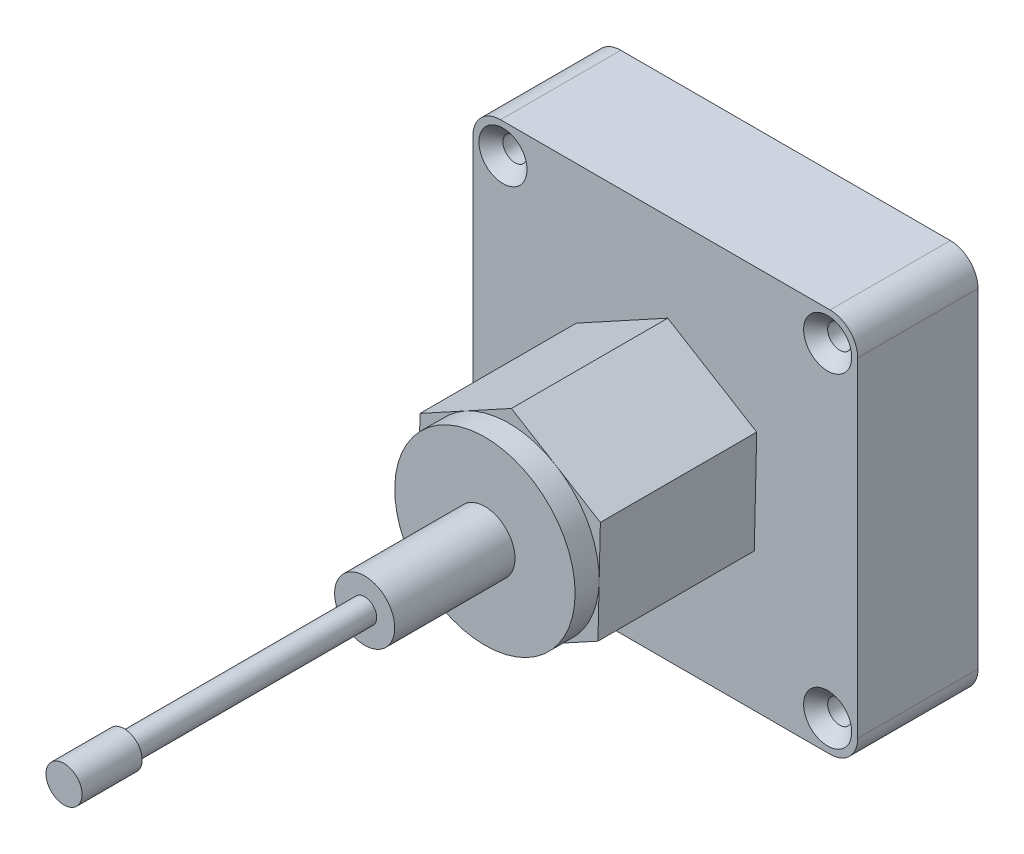
SolidWorks part; units mm, degrees
material "Copper"
ref_plane "Front Plane" through (0, 0, 0) normal (0, 0, 1) x (1, 0, 0)
ref_plane "Top Plane" through (0, 0, 0) normal (0, 1, 0) x (1, 0, 0)
ref_plane "Right Plane" through (0, 0, 0) normal (1, 0, 0) x (0, 0, -1)
sketch "Sketch1" plane through (0, 0, 0) normal (0, 0, 1) x (1, 0, 0)
  line L1 (7.3971, -4.5036) -> (7.5988, 4.1543)
  line L2 (7.5988, 4.1543) -> (0.2017, 8.6579)
  line L3 (0.2017, 8.6579) -> (-7.3971, 4.5036)
  line L4 (-7.3971, 4.5036) -> (-7.5988, -4.1543)
  line L5 (-7.5988, -4.1543) -> (-0.2017, -8.6579)
  line L6 (-0.2017, -8.6579) -> (7.3971, -4.5036)
  circle A1 centre (0, 0) radius 7.5 construction
  dimension "D2" = 15
extrude "Boss-Extrude1" add sketch "Sketch1" against normal blind 2
sketch "Sketch2" plane through (0, 0, 0) normal (0, 0, 1) x (1, 0, 0)
  circle A0 centre (0, 0) radius 7.5
  dimension "D1" = 15
extrude "Boss-Extrude2" add sketch "Sketch2" along normal blind 2
sketch "Sketch3" plane through (0, 0, 2) normal (0, 0, 1) x (1, 0, 0)
  circle A0 centre (0, 0) radius 2.5
  dimension "D1" = 5
extrude "Boss-Extrude3" add sketch "Sketch3" along normal blind 10
sketch "Sketch4" plane through (0, 0, 12) normal (0, 0, 1) x (1, 0, 0)
  circle A0 centre (0, 0) radius 1
  dimension "D1" = 2
extrude "Boss-Extrude4" add sketch "Sketch4" along normal blind 20
sketch "Sketch5" plane through (0, 0, 32) normal (0, 0, 1) x (1, 0, 0)
  circle A1 centre (0, 0) radius 1.5
  dimension "D1" = 3
extrude "Boss-Extrude5" add sketch "Sketch5" along normal blind 5
sketch "Sketch6" plane through (0, 0, -2) normal (0, 0, -1) x (-1, 0, 0)
  line L6 (0, 0) -> (0.1008, -4.329) construction
  line L7 (-7.5988, 4.1543) -> (-0.2017, 8.6579)
  line L8 (-0.2017, 8.6579) -> (7.3971, 4.5036)
  line L9 (7.3971, 4.5036) -> (7.5988, -4.1543)
  line L10 (7.5988, -4.1543) -> (0.2017, -8.6579)
  line L11 (0.2017, -8.6579) -> (-7.3971, -4.5036)
  line L12 (-7.3971, -4.5036) -> (-7.5988, 4.1543)
extrude "Boss-Extrude6" add sketch "Sketch6" along normal blind 11
sketch "Sketch7" plane through (0, 0, -13) normal (0, 0, -1) x (-1, 0, 0)
  line L0 (-13.5, 13.5) -> (-13.5, -13.5) construction
  line L1 (-13.7, 16) -> (13.7, 16)
  line L2 (-16, 13.7) -> (-16, -13.7)
  line L3 (-13.7, -16) -> (13.7, -16)
  line L4 (16, 13.7) -> (16, -13.7)
  line L5 (-16, 16) -> (16, -16) construction
  line L6 (-16, -16) -> (16, 16) construction
  line L7 (-13.5, -13.5) -> (13.5, -13.5) construction
  line L8 (13.5, -13.5) -> (13.5, 13.5) construction
  line L9 (13.5, 13.5) -> (-13.5, 13.5) construction
  arc A0 (13.7, 16) -> (16, 13.7) centre (13.7, 13.7) cw
  arc A1 (13.7, -16) -> (16, -13.7) centre (13.7, -13.7) ccw
  arc A2 (-13.7, -16) -> (-16, -13.7) centre (-13.7, -13.7) cw
  arc A3 (-16, 13.7) -> (-13.7, 16) centre (-13.7, 13.7) cw
  circle A8 centre (-13.5, 13.5) radius 1
  circle A9 centre (13.5, 13.5) radius 1
  circle A10 centre (13.5, -13.5) radius 1
  circle A11 centre (-13.5, -13.5) radius 1
  point P0 (0, 0)
  dimension "D3" = 2.3
  dimension "D4" = 2
  dimension "D1" = 32
  dimension "D2" = 32
  dimension "D5" = 2.5
extrude "Boss-Extrude7" add sketch "Sketch7" along normal blind 10
sketch "Sketch10" plane through (0, 0, 0) normal (0, 1, 0) x (1, 0, 0)
  line L0 (0, 23) -> (0, -37) construction
  line L1 (-13.7, 23) -> (13.7, 23) construction
  line L2 (-1.5, -37) -> (1.5, -37) construction
chamfer "Chamfer1" distance 1 angle 45 4 edges at (12.5, -13.5, -13) (12.5, 13.5, -13) (-14.5, 13.5, -13) (-14.5, -13.5, -13)
